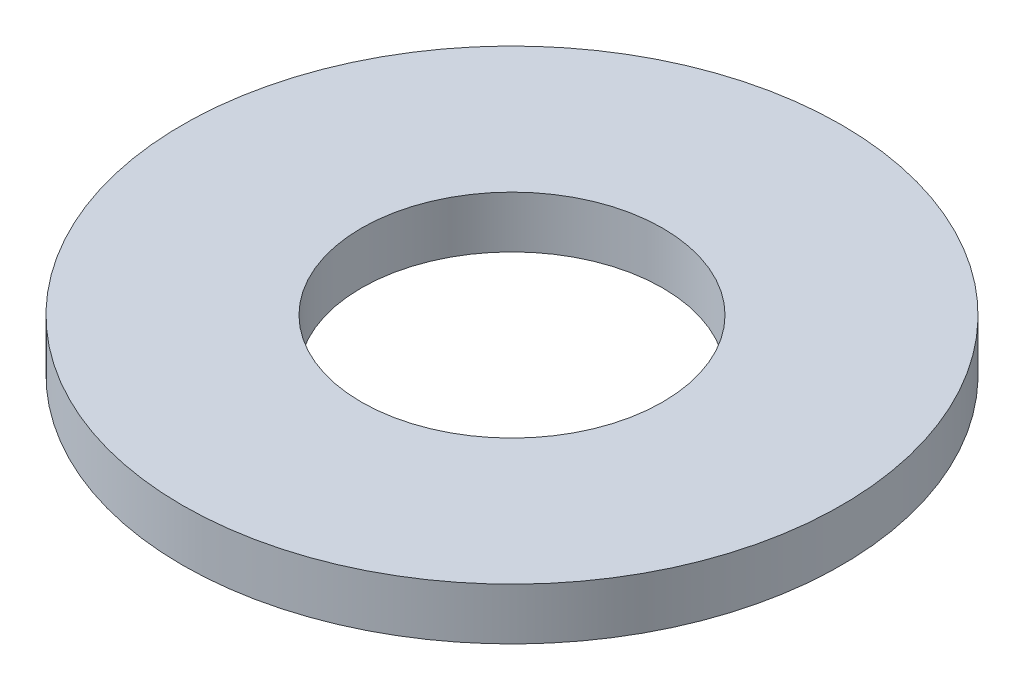
SolidWorks part; units mm, degrees
material "Plain Carbon Steel"
ref_plane "Front Plane" through (0, 0, 0) normal (0, 0, 1) x (1, 0, 0)
ref_plane "Top Plane" through (0, 0, 0) normal (0, 1, 0) x (1, 0, 0)
ref_plane "Right Plane" through (0, 0, 0) normal (1, 0, 0) x (0, 0, -1)
sketch "Sketch1" plane through (0, 0, 0) normal (0, 1, 0) x (1, 0, 0)
  circle A0 centre (0, 0) radius 1.6
  circle A1 centre (0, 0) radius 3.5
  dimension "D1" = 3.2
  dimension "D2" = 7
extrude "Boss-Extrude1" add sketch "Sketch1" along normal blind 0.55
